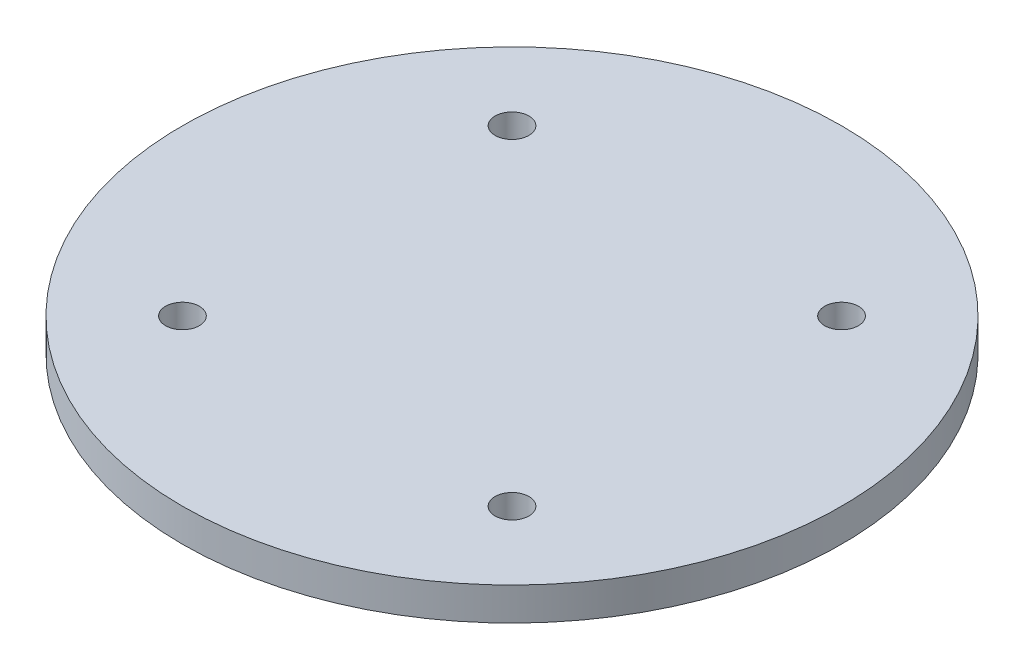
SolidWorks part; units mm, degrees
ref_plane "Спереди" through (0, 0, 0) normal (0, 0, 1) x (1, 0, 0)
ref_plane "Сверху" through (0, 0, 0) normal (0, 1, 0) x (1, 0, 0)
ref_plane "Справа" through (0, 0, 0) normal (1, 0, 0) x (0, 0, -1)
sketch "Эскиз1" plane through (0, 0, 0) normal (0, 1, 0) x (1, 0, 0)
  circle A0 centre (0, 0) radius 20
  dimension "D1" = 40
extrude "Бобышка-Вытянуть1" add sketch "Эскиз1" along normal blind 2
sketch "Эскиз2" plane through (0, 2, 0) normal (0, 1, 0) x (1, 0, 0)
  line L0 (0, 24.6684) -> (0, -27.4252) construction
  line L1 (-24.6684, 0) -> (24.382, 0) construction
  line L2 (-10, -10) -> (10, -10) construction
  line L3 (-10, -10) -> (-10, 10) construction
  line L4 (-10, 10) -> (10, 10) construction
  line L5 (10, -10) -> (10, 10) construction
  dimension "D1" = 20
  dimension "D2" = 10
  dimension "D3" = 10
hole_wizard "Отверстие обработанное метчиком M2.51" positions "Эскиз3" profile "Эскиз4" tap size "M2.5" standard "ISO" end condition through all
sketch "Эскиз3" plane through (0, 2, 0) normal (0, 1, 0) x (1, 0, 0)
  point P0 (-10, 10)
  point P3 (10, 10)
  point P6 (-10, -10)
  point P9 (10, -10)
sketch "Эскиз4" plane through (-10, 2, -10) normal (1, 0, 0) x (0, 0, 1)
  line L0 (0, 0) -> (0, 2)
  line L1 (0, 2) -> (1.025, 2)
  line L2 (1.025, 2) -> (1.025, 0)
  line L5 (1.025, 0) -> (0, 0)
  line L11 (0, -6.35) -> (0, 107.95) construction
  dimension "Диаметр проходного сверла" = 2.05
  dimension "Глубина проходного сверла" = 2
cosmetic thread "Отверстие резьбы1"
cosmetic thread "Отверстие резьбы2"
cosmetic thread "Отверстие резьбы3"
cosmetic thread "Отверстие резьбы4"
